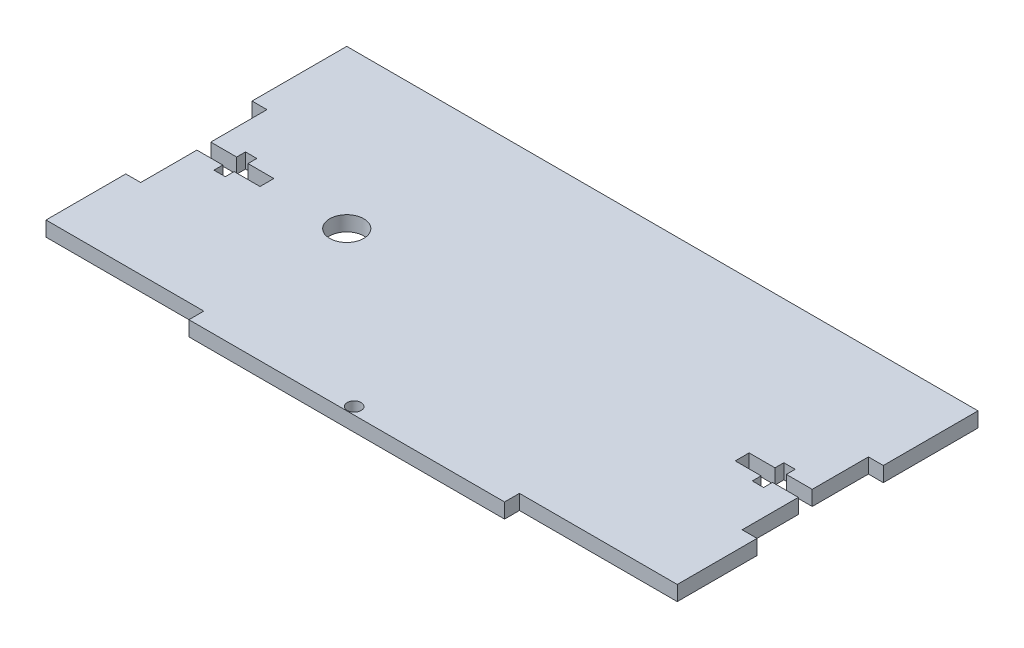
SolidWorks part; units mm, degrees
ref_plane "Front Plane" through (0, 0, 0) normal (0, 0, 1) x (1, 0, 0)
ref_plane "Top Plane" through (0, 0, 0) normal (0, 1, 0) x (1, 0, 0)
ref_plane "Right Plane" through (0, 0, 0) normal (1, 0, 0) x (0, 0, -1)
sketch "Sketch1" plane through (0, 0, 0) normal (0, 1, 0) x (1, 0, 0)
  line L1 (-63.5, -31.75) -> (63.5, -31.75)
  line L2 (-63.5, -31.75) -> (-63.5, 31.75)
  line L3 (-63.5, 31.75) -> (63.5, 31.75)
  line L4 (63.5, -31.75) -> (63.5, 31.75)
  line L5 (-63.5, -31.75) -> (63.5, 31.75) construction
  line L6 (-63.5, 31.75) -> (63.5, -31.75) construction
  point P0 (0, 0)
  dimension "D1" = 127
  dimension "10" = 63.5
extrude "Boss-Extrude1" add sketch "Sketch1" along normal blind 2.9972
sketch "Sketch2" plane through (0, 2.9972, 0) normal (0, 1, 0) x (1, 0, 0)
  line L23 (-63.5, 31.75) -> (-63.5, -31.75) construction
  line L24 (-63.5, -31.75) -> (-31.75, -31.75)
  line L25 (-63.5, -31.75) -> (-63.5, -28.7528)
  line L26 (-63.5, -28.7528) -> (-31.75, -28.7528)
  line L27 (-31.75, -31.75) -> (-31.75, -28.7528)
  line L42 (-63.5, 12.7) -> (-60.5028, 12.7)
  line L43 (-63.5, 12.7) -> (-63.5, -12.7)
  line L46 (-63.5, -12.7) -> (-60.5028, -12.7)
  line L47 (-60.5028, 12.7) -> (-60.5028, 1.397)
  line L54 (-63.5, 0) -> (63.5, 0) construction
  line L55 (63.5, -31.75) -> (63.5, 31.75) construction
  line L61 (-53.0098, 1.397) -> (-47.8028, 1.397)
  line L62 (-60.5028, -1.397) -> (-55.2958, -1.397)
  line L68 (-60.5028, 1.397) -> (-55.2958, 1.397)
  line L73 (-47.8028, -1.397) -> (-47.8028, 1.397)
  line L74 (-60.5028, -1.397) -> (-47.8028, 1.397) construction
  line L78 (-60.5028, 1.397) -> (-47.8028, -1.397) construction
  line L82 (-55.2958, -3.175) -> (-53.0098, -3.175)
  line L83 (-55.2958, -3.175) -> (-55.2958, -1.397)
  line L90 (-55.2958, 3.175) -> (-53.0098, 3.175)
  line L91 (-53.0098, -3.175) -> (-53.0098, -1.397)
  line L96 (-55.2958, -3.175) -> (-53.0098, 3.175) construction
  line L97 (-55.2958, 3.175) -> (-53.0098, -3.175) construction
  line L101 (-55.2958, 1.397) -> (-55.2958, 3.175)
  line L108 (-53.0098, 1.397) -> (-53.0098, 3.175)
  line L109 (0, 31.75) -> (0, -31.75) construction
  line L114 (-53.0098, -1.397) -> (-47.8028, -1.397)
  line L115 (63.5, 31.75) -> (-63.5, 31.75) construction
  line L128 (-63.5, -31.75) -> (63.5, -31.75) construction
  line L129 (-60.5028, -1.397) -> (-60.5028, -12.7)
  line L134 (63.5, -28.7528) -> (31.75, -28.7528)
  line L135 (31.75, -31.75) -> (31.75, -28.7528)
  line L140 (63.5, -31.75) -> (31.75, -31.75)
  line L141 (63.5, -31.75) -> (63.5, -28.7528)
  line L142 (60.5028, -1.397) -> (60.5028, -12.7)
  line L143 (63.5, -12.7) -> (60.5028, -12.7)
  line L144 (63.5, 12.7) -> (63.5, -12.7)
  line L145 (63.5, 12.7) -> (60.5028, 12.7)
  line L146 (60.5028, 12.7) -> (60.5028, 1.397)
  line L147 (60.5028, 1.397) -> (55.2958, 1.397)
  line L148 (55.2958, 1.397) -> (55.2958, 3.175)
  line L149 (55.2958, 3.175) -> (53.0098, 3.175)
  line L150 (53.0098, 1.397) -> (53.0098, 3.175)
  line L151 (53.0098, 1.397) -> (47.8028, 1.397)
  line L152 (47.8028, -1.397) -> (47.8028, 1.397)
  line L153 (53.0098, -1.397) -> (47.8028, -1.397)
  line L154 (53.0098, -3.175) -> (53.0098, -1.397)
  line L155 (55.2958, -3.175) -> (53.0098, -3.175)
  line L156 (55.2958, -3.175) -> (55.2958, -1.397)
  line L157 (60.5028, -1.397) -> (55.2958, -1.397)
  circle A7 centre (0, -30.2514) radius 1.397
  point P5 (0, 0)
  point P6 (31.75, -30.2514)
  point P7 (0.9941, -30.2514)
  point P8 (0, 0)
  point P15 (-63.5, 0)
  point P20 (-54.1528, 0)
  point P26 (-54.1528, 0)
  point P69 (0, 0)
  dimension "D8" = 2.794
  dimension "D1" = 2.9972
  dimension "D2" = 25.4
  dimension "D3" = 31.75
  dimension "D4" = 12.7
  dimension "D5" = 2.794
  dimension "D6" = 2.286
  dimension "D7" = 6.35
sketch "Sketch3" plane through (0, 2.9972, 0) normal (0, 1, 0) x (1, 0, 0)
  line L0 (-63.5, -31.75) -> (63.5, -31.75) construction
  line L9 (-63.5, 31.75) -> (-63.5, -31.75) construction
  line L12 (-40.64, 0) -> (-22.86, 0) construction
  circle A0 centre (-31.75, 0) radius 12.7 construction
  circle A2 centre (-31.75, 0) radius 3.429
  point P21 (-31.75, 0)
  dimension "D1" = 25.4
  dimension "D6" = 6.858
  dimension "D3" = 31.75
  dimension "D4" = 31.75
  dimension "D9" = 17.78
extrude "Cut-Extrude1" cut sketch "Sketch2" against normal up to next
extrude "Cut-Extrude2" cut sketch "Sketch3" against normal up to next
